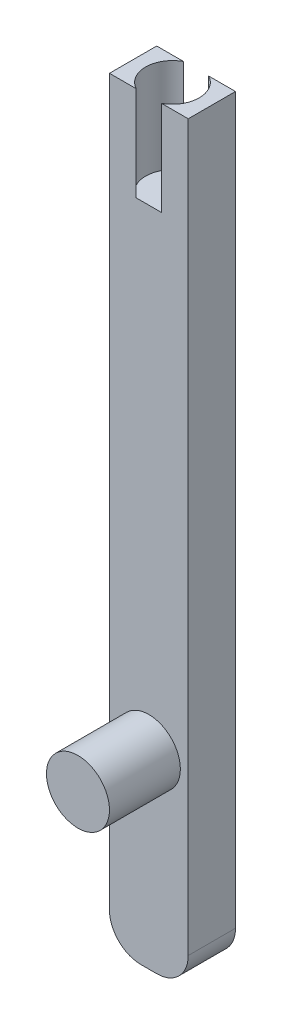
SolidWorks part; units mm, degrees
ref_plane "Спереди" through (0, 0, 0) normal (0, 0, 1) x (1, 0, 0)
ref_plane "Сверху" through (0, 0, 0) normal (0, 1, 0) x (1, 0, 0)
ref_plane "Справа" through (0, 0, 0) normal (1, 0, 0) x (0, 0, -1)
sketch "Эскиз1" plane through (0, 0, 0) normal (0, 0, 1) x (1, 0, 0)
  line L1 (-1, 0) -> (-1.5, 0)
  line L2 (0, 1) -> (0, 24)
  line L3 (0, 24) -> (-2.5, 24)
  line L4 (-2.5, 1) -> (-2.5, 24)
  arc A0 (-1, 0) -> (0, 1) centre (-1, 1) ccw
  arc A1 (-1.5, 0) -> (-2.5, 1) centre (-1.5, 1) cw
  point P7 (0, 0)
  point P10 (-2.5, 0)
  dimension "D3" = 1
  dimension "D1" = 24
  dimension "D2" = 2.5
extrude "Бобышка-Вытянуть1" add sketch "Эскиз1" along normal blind 1.5
sketch "Эскиз2" plane through (0, 0, 1.5) normal (0, 0, 1) x (1, 0, 0)
  line L0 (-1.25, 24) -> (-1.25, 6) construction
  line L1 (0, 24) -> (-2.5, 24) construction
  circle A0 centre (-1.25, 6) radius 1
  dimension "D2" = 2
  dimension "D1" = 18
extrude "Бобышка-Вытянуть2" add sketch "Эскиз2" along normal blind 2.25
sketch "Эскиз3" plane through (0, 24, 0) normal (0, 1, 0) x (1, 0, 0)
  line L0 (-2.5, -1.5) -> (0, 0) construction
  circle A0 centre (-1.25, -0.75) radius 0.85
  dimension "D1" = 1.7
extrude "Вырез-Вытянуть1" cut sketch "Эскиз3" against normal blind 3
